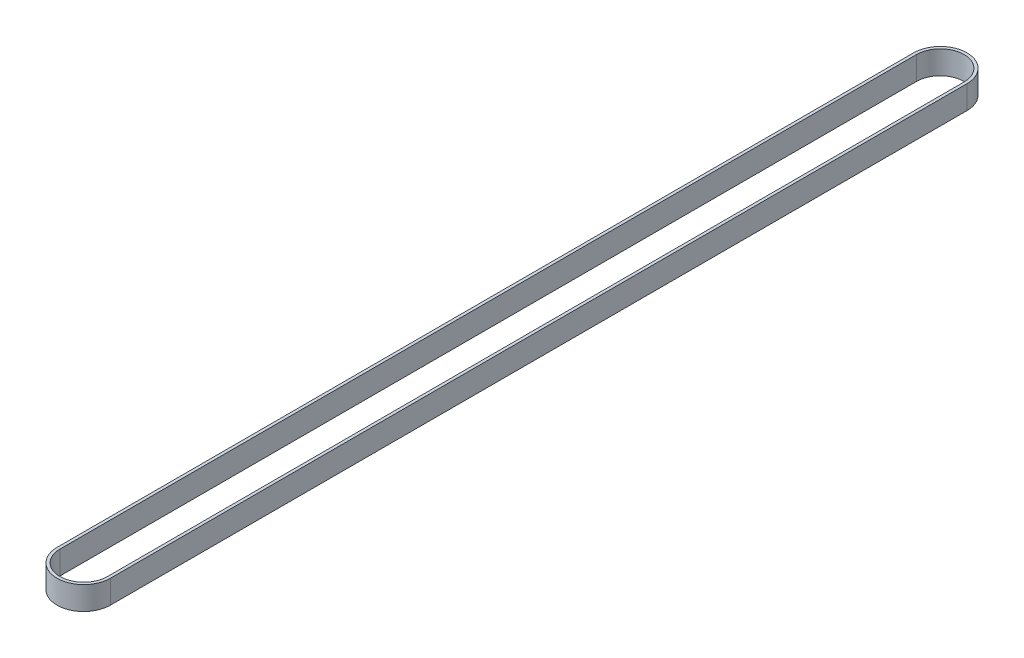
SolidWorks part; units mm, degrees
material "天然橡胶"
ref_plane "前视基准面" through (0, 0, 0) normal (0, 0, 1) x (1, 0, 0)
ref_plane "上视基准面" through (0, 0, 0) normal (0, 1, 0) x (1, 0, 0)
ref_plane "右视基准面" through (0, 0, 0) normal (1, 0, 0) x (0, 0, -1)
other "Configuration Table"
sketch "草图1" plane through (0, 0, 0) normal (0, 1, 0) x (1, 0, 0)
  line L0 (0, -110.05) -> (0, 110.05) construction
  line L1 (-6.86, -110.05) -> (-6.86, 110.05)
  line L2 (6.86, -110.05) -> (6.86, 110.05)
  line L3 (0, -110.05) -> (0, 110.05) construction
  line L4 (-6.11, -110.05) -> (-6.11, 110.05)
  line L5 (6.11, -110.05) -> (6.11, 110.05)
  arc A0 (-6.86, -110.05) -> (6.86, -110.05) centre (0, -110.05) ccw
  arc A1 (6.86, 110.05) -> (-6.86, 110.05) centre (0, 110.05) ccw
  arc A2 (-6.11, -110.05) -> (6.11, -110.05) centre (0, -110.05) ccw
  arc A3 (6.11, 110.05) -> (-6.11, 110.05) centre (0, 110.05) ccw
  point P2 (0, 0)
  point P9 (0, 0)
  dimension "D3" = 6.11
  dimension "D4" = 6.86
  dimension "D1" = 220.1
  dimension "D2" = 220.1
extrude "凸台-拉伸1" add sketch "草图1" along normal blind 6
